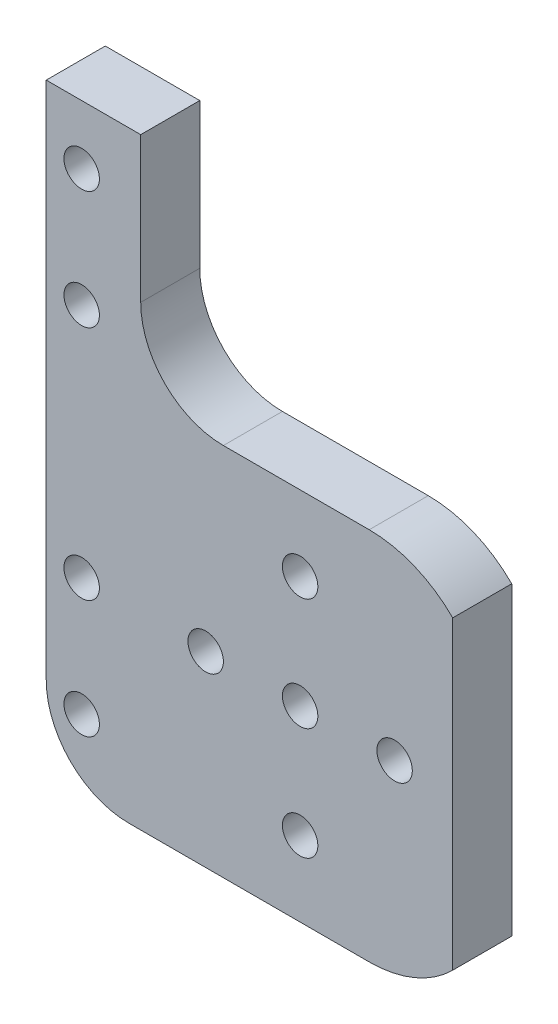
SolidWorks part; units mm, degrees
ref_plane "Alzado" through (0, 0, 0) normal (0, 0, 1) x (1, 0, 0)
ref_plane "Planta" through (0, 0, 0) normal (0, 1, 0) x (1, 0, 0)
ref_plane "Vista lateral" through (0, 0, 0) normal (1, 0, 0) x (0, 0, -1)
sketch "Croquis1" plane through (0, 0, 0) normal (0, 0, 1) x (1, 0, 0)
  line L0 (-28.7905, 20.9269) -> (-28.7905, -0.0731)
  line L1 (-28.7905, -0.0731) -> (-28.7905, -3.7731)
  line L2 (-13.7905, 20.9269) -> (-1.4405, 20.9269)
  line L3 (-21.7905, -10.7731) -> (-1.4405, -10.7731)
  line L4 (5.6305, 17.9979) -> (5.6305, -7.8442)
  line L5 (-28.7905, -3.7731) -> (-28.7905, 40.2269)
  line L6 (-28.7905, 40.2269) -> (-20.7905, 40.2269)
  line L7 (-20.7905, 27.9269) -> (-20.7905, 40.2269)
  circle A0 centre (-7.2905, 5.0769) radius 1.5
  circle A1 centre (-15.2905, 5.0769) radius 1.5
  circle A2 centre (-7.2905, -4.4231) radius 1.5
  circle A3 centre (0.7095, 5.0769) radius 1.5
  circle A4 centre (-7.2905, 14.5769) radius 1.5
  arc A7 (-1.4405, -10.7731) -> (5.6305, -7.8442) centre (-1.4405, -0.7731) ccw
  arc A8 (5.6305, 17.9979) -> (-1.4405, 20.9269) centre (-1.4405, 10.9269) ccw
  arc A9 (-20.7905, 27.9269) -> (-13.7905, 20.9269) centre (-13.7905, 27.9269) ccw
  arc A11 (-21.7905, -10.7731) -> (-28.7905, -3.7731) centre (-21.7905, -3.7731) cw
  circle A21 centre (-25.7905, 25.2269) radius 1.5
  circle A22 centre (-25.7905, 35.2269) radius 1.5
  circle A23 centre (-25.7905, -4.7731) radius 1.5
  circle A24 centre (-25.7905, 5.2269) radius 1.5
extrude "Saliente-Extruir1" add sketch "Croquis1" along normal blind 5
